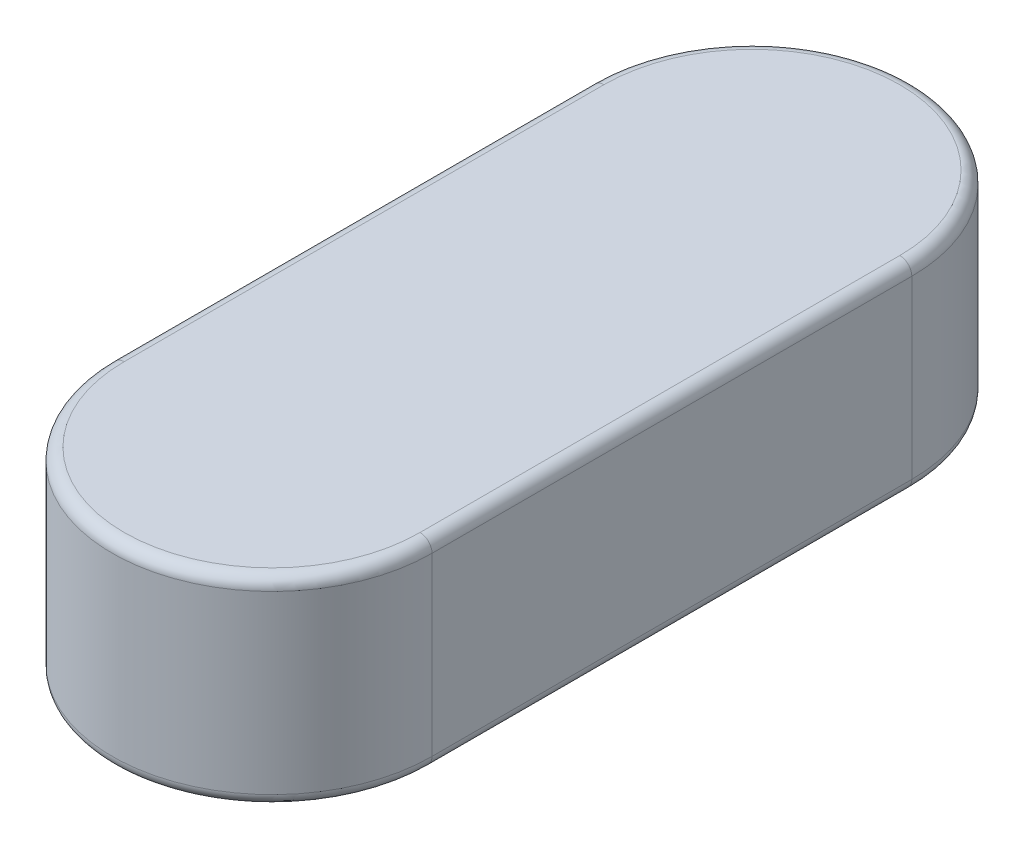
SolidWorks part; units mm, degrees
material "AISI 304"
ref_plane "Спереди" through (0, 0, 0) normal (0, 0, 1) x (1, 0, 0)
ref_plane "Сверху" through (0, 0, 0) normal (0, 1, 0) x (1, 0, 0)
ref_plane "Справа" through (0, 0, 0) normal (1, 0, 0) x (0, 0, -1)
sketch "Эскиз1" plane through (0, 0, 0) normal (0, 1, 0) x (1, 0, 0)
  line L0 (0, 0) -> (0, 24) construction
  line L1 (-8, 0) -> (-8, 24)
  line L2 (8, 0) -> (8, 24)
  line L3 (0, -8) -> (0, 32) construction
  arc A0 (-8, 0) -> (8, 0) centre (0, 0) ccw
  arc A1 (8, 24) -> (-8, 24) centre (0, 24) ccw
  point P3 (0, 12)
  dimension "D1" = 8
  dimension "D2" = 24
  dimension "D3" = 40
  dimension "D4" = 16
extrude "Бобышка-Вытянуть1" add sketch "Эскиз1" along normal blind 10
fillet "Скругление1" radius 0.6 8 edges at (8, 0, -12) (0, 0, -32) (-8, 0, -12) (0, 0, 8) (-8, 10, -12) (0, 10, -32) (8, 10, -12) (0, 10, 8)
